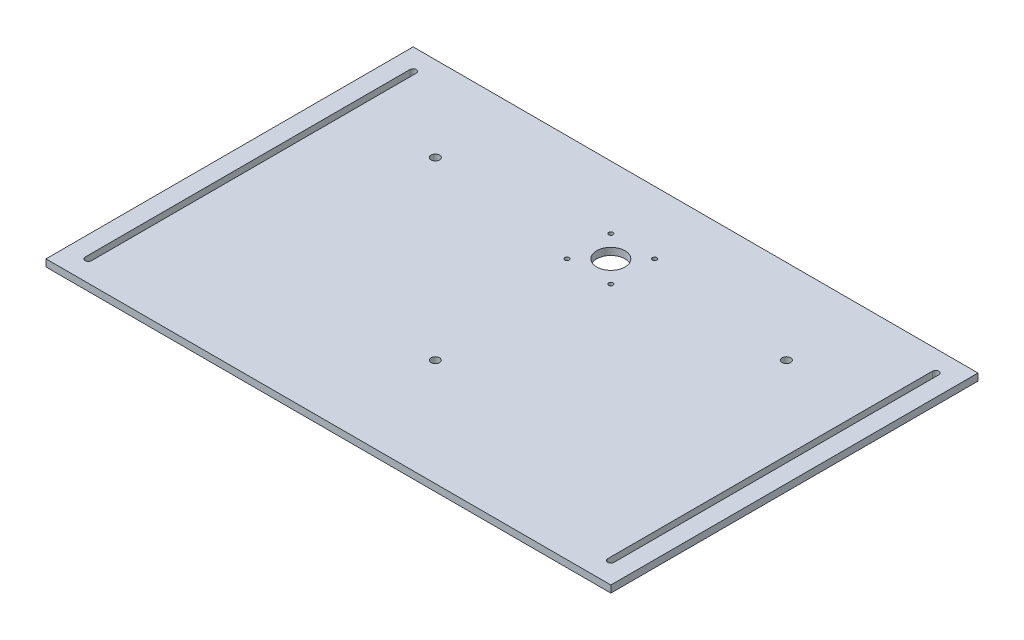
SolidWorks part; units mm, degrees
ref_plane "前基準面" through (0, 0, 0) normal (0, 0, 1) x (1, 0, 0)
ref_plane "上基準面" through (0, 0, 0) normal (0, 1, 0) x (1, 0, 0)
ref_plane "右基準面" through (0, 0, 0) normal (1, 0, 0) x (0, 0, -1)
sketch "草圖1" plane through (0, 0, 0) normal (0, 1, 0) x (1, 0, 0)
  line L0 (200, 60) -> (170, 60) construction
  line L1 (200, 160) -> (-200, 160) construction
  line L2 (200, 160) -> (200, -160) construction
  line L3 (200, -160) -> (-200, -160) construction
  line L4 (-200, 160) -> (-200, -160) construction
  line L5 (0, -160) -> (0, 160) construction
  line L6 (200, 0) -> (-200, 0) construction
  line L7 (-200, 160) -> (200, 160) construction
  line L8 (-200, 160) -> (-200, 130) construction
  line L9 (-200, 130) -> (200, 130) construction
  line L10 (200, 160) -> (200, 130) construction
  line L11 (-200, 130) -> (-170, 130) construction
  line L12 (-200, 130) -> (-200, -130) construction
  line L13 (-200, -130) -> (-170, -130) construction
  line L14 (-170, 130) -> (-170, -130) construction
  line L15 (200, -160) -> (-200, -160) construction
  line L16 (200, -160) -> (200, -130) construction
  line L17 (200, -130) -> (-200, -130) construction
  line L18 (-200, -160) -> (-200, -130) construction
  line L19 (200, -130) -> (170, -130) construction
  line L20 (200, -130) -> (200, 130) construction
  line L21 (200, 130) -> (170, 130) construction
  line L22 (170, -130) -> (170, 130) construction
  line L23 (-200, 130) -> (-170, 130) construction
  line L24 (-200, 130) -> (-200, 60) construction
  line L25 (-200, 60) -> (-170, 60) construction
  line L26 (-170, 130) -> (-170, 60) construction
  line L27 (170, 130) -> (170, 60) construction
  line L29 (200, 130) -> (200, 60) construction
  line L30 (-200, -60) -> (-170, -60) construction
  line L31 (-170, -130) -> (-170, -60) construction
  line L32 (-200, -130) -> (-170, -130) construction
  line L33 (-200, -130) -> (-200, -60) construction
  line L34 (200, -130) -> (200, -60) construction
  line L35 (170, -130) -> (170, -60) construction
  line L36 (200, -60) -> (170, -60) construction
  line L37 (200, -130) -> (170, -130) construction
  line L40 (-200, 130) -> (-200, -130)
  line L42 (200, 130) -> (200, -130)
  line L43 (-200, 130) -> (200, 130)
  line L44 (-200, 130) -> (-200, -130)
  line L45 (-200, -130) -> (200, -130)
  line L46 (200, 130) -> (200, -130)
  point P0 (0, 0)
  dimension "D1" = 400
  dimension "D2" = 320
  dimension "D4" = 30
  dimension "D6" = 30
  dimension "D7" = 70
extrude "填料-伸長1" add sketch "草圖1" along normal blind 5 contours L40 L45 L42 L43
sketch "草圖2" plane through (0, 5, 0) normal (0, 1, 0) x (1, 0, 0)
  line L0 (-185, 130) -> (-185, -130) construction
  line L1 (-200, 130) -> (200, 130) construction
  line L2 (-200, -130) -> (200, -130) construction
  line L3 (185, -130) -> (185, 130) construction
  line L4 (-185, 115) -> (-185, -115) construction
  line L5 (-182.75, 115) -> (-182.75, -115)
  line L6 (-187.25, 115) -> (-187.25, -115)
  line L7 (-200, 60) -> (-170, 60) construction
  line L8 (200, 0) -> (-200, 0) construction
  line L9 (0, -160) -> (0, 160) construction
  line L10 (0, -160) -> (0, 160) construction
  line L11 (185, 115) -> (185, -115) construction
  line L12 (182.75, 115) -> (182.75, -115)
  line L13 (187.25, 115) -> (187.25, -115)
  arc A0 (-182.75, 115) -> (-187.25, 115) centre (-185, 115) ccw
  arc A1 (-187.25, -115) -> (-182.75, -115) centre (-185, -115) ccw
  arc A2 (182.75, 115) -> (187.25, 115) centre (185, 115) cw
  arc A3 (187.25, -115) -> (182.75, -115) centre (185, -115) cw
  point P10 (-185, 0)
  point P17 (-185, 60)
  point P25 (185, 0)
  dimension "D1" = 4.5
  dimension "D2" = 230
extrude "除料-伸長1" cut sketch "草圖2" against normal through all
sketch "草圖3" plane through (0, 5, 0) normal (0, 1, 0) x (1, 0, 0)
  line L0 (0, -160) -> (0, 160) construction
  line L5 (-200, 130) -> (-200, -130) construction
  line L10 (-200, 190) -> (200, 190) construction
  line L11 (-200, 190) -> (-200, 130) construction
  line L12 (-200, 130) -> (200, 130) construction
  line L13 (-21.15, 85.5) -> (-15.5, 91.15) construction
  line L14 (-15.5, 91.15) -> (15.5, 91.15) construction
  line L15 (-21.15, 85.5) -> (-21.15, 54.5) construction
  line L16 (-15.5, 48.85) -> (15.5, 48.85) construction
  line L17 (21.15, 85.5) -> (21.15, 54.5) construction
  line L18 (15.5, 91.15) -> (21.15, 85.5) construction
  line L19 (15.5, 48.85) -> (21.15, 54.5) construction
  line L20 (-21.15, 54.5) -> (-15.5, 48.85) construction
  line L21 (200, 190) -> (200, 130) construction
  line L22 (-127.3048, 73) -> (-121.3048, 73) construction
  line L23 (-121.3048, 73) -> (-121.3048, 67) construction
  line L24 (-121.3048, 67) -> (-127.3048, 67) construction
  line L25 (-3, -57.3048) -> (-3, -51.3048) construction
  line L26 (-3, -51.3048) -> (3, -51.3048) construction
  line L27 (3, -51.3048) -> (3, -57.3048) construction
  line L28 (127.3048, 67) -> (121.3048, 67) construction
  line L29 (121.3048, 67) -> (121.3048, 73) construction
  line L30 (121.3048, 73) -> (127.3048, 73) construction
  line L31 (3, 197.3048) -> (3, 191.3048) construction
  line L32 (3, 191.3048) -> (-3, 191.3048) construction
  line L33 (-3, 191.3048) -> (-3, 197.3048) construction
  line L34 (-121.3048, 70) -> (121.3048, 70) construction
  line L35 (0, -51.3048) -> (0, 191.3048) construction
  circle A4 centre (-15.5, 85.5) radius 1.55
  circle A5 centre (15.5, 85.5) radius 1.55
  circle A6 centre (-15.5, 54.5) radius 1.55
  circle A7 centre (15.5, 54.5) radius 1.55
  circle A8 centre (0, 70) radius 10
  arc A9 (-3, 197.3048) -> (-127.3048, 73) centre (2, 68) ccw construction
  arc A10 (-127.3048, 67) -> (-3, -57.3048) centre (2, 72) ccw construction
  arc A11 (3, -57.3048) -> (127.3048, 67) centre (-2, 72) ccw construction
  arc A12 (127.3048, 73) -> (3, 197.3048) centre (-2, 68) ccw construction
  circle A13 centre (-124.3048, 70) radius 3
  circle A14 centre (124.3048, 70) radius 3
  circle A15 centre (0, -54.3048) radius 3
  point P0 (0, 70)
  point P32 (0, 91.15)
  point P50 (-21.15, 70)
  point P51 (0, 70)
  dimension "D2" = 42.3
  dimension "D10" = 45
  dimension "D5" = 3.1
  dimension "D11" = 20
  dimension "D12" = 129.4014
  dimension "D17" = 6
  dimension "D18" = 6
  dimension "D1" = 42.3
  dimension "D3" = 31
  dimension "D4" = 31
  dimension "D7" = 5.65
  dimension "D8" = 60
  dimension "D9" = 60
  dimension "D16" = 4
  dimension "D6" = 5.65
  dimension "D13" = 6
  dimension "D14" = 6
  dimension "D15" = 4
extrude "除料-伸長2" cut sketch "草圖3" against normal through all
